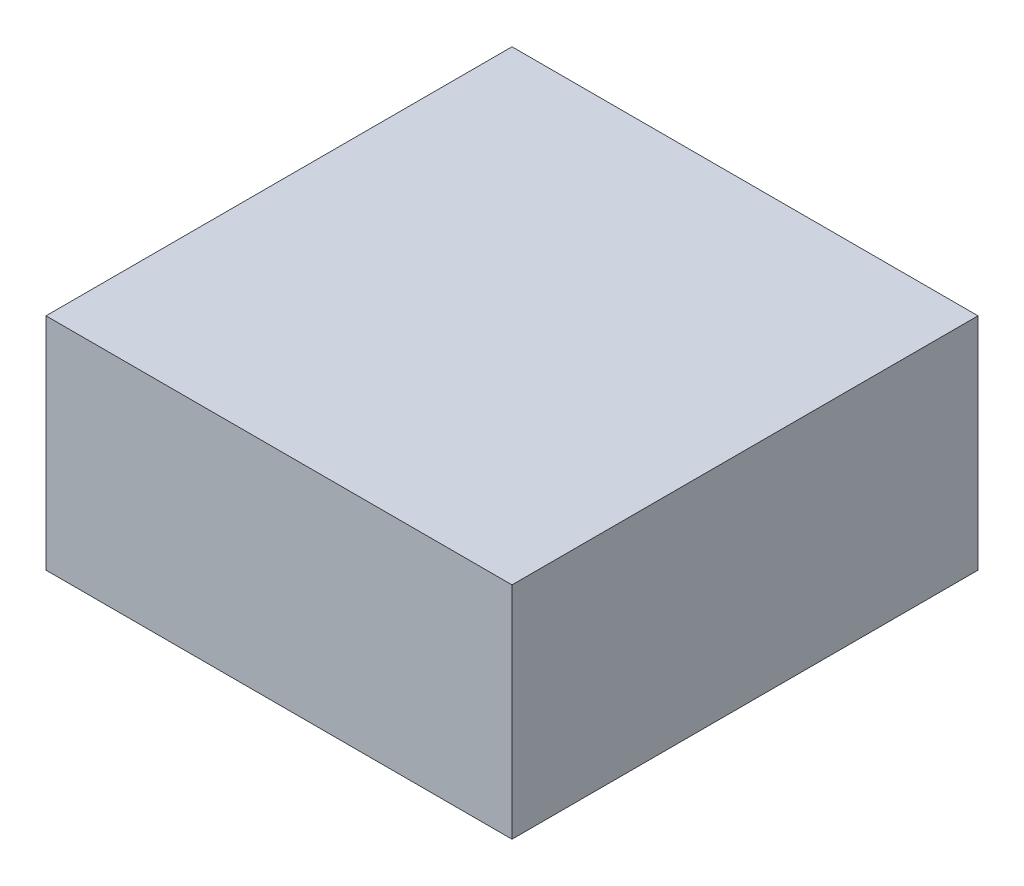
SolidWorks part; units mm, degrees
ref_plane "Front Plane" through (0, 0, 0) normal (0, 0, 1) x (1, 0, 0)
ref_plane "Top Plane" through (0, 0, 0) normal (0, 1, 0) x (1, 0, 0)
ref_plane "Right Plane" through (0, 0, 0) normal (1, 0, 0) x (0, 0, -1)
sketch "Sketch1" plane through (0, 0, 0) normal (0, 1, 0) x (1, 0, 0)
  line L1 (-275, -275) -> (275, -275)
  line L2 (-275, -275) -> (-275, 275)
  line L3 (-275, 275) -> (275, 275)
  line L4 (275, -275) -> (275, 275)
  line L5 (-275, -275) -> (275, 275) construction
  line L6 (-275, 275) -> (275, -275) construction
  point P0 (0, 0)
  dimension "D1" = 550
extrude "Boss-Extrude1" add sketch "Sketch1" along normal blind 260
